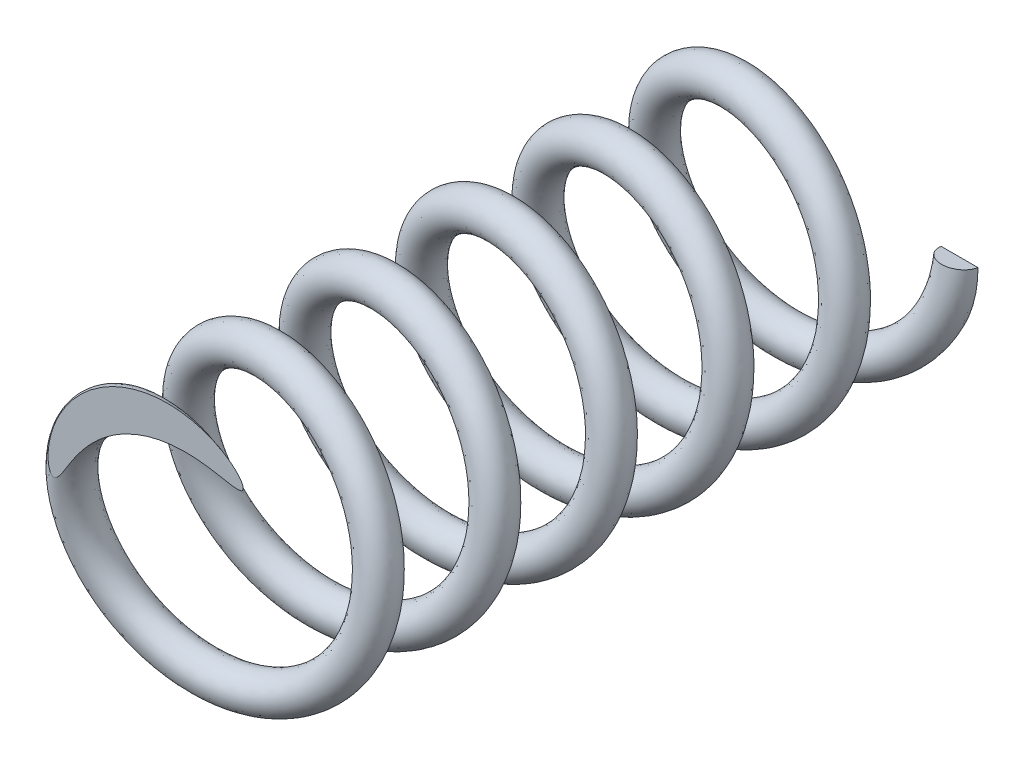
SolidWorks part; units mm, degrees
material "Alloy Steel"
ref_plane "Front Plane" through (0, 0, 0) normal (0, 0, 1) x (1, 0, 0)
ref_plane "Top Plane" through (0, 0, 0) normal (0, 1, 0) x (1, 0, 0)
ref_plane "Right Plane" through (0, 0, 0) normal (1, 0, 0) x (0, 0, -1)
ref_plane "Plane1" through (0, 0, 0) normal (0, 0, 1) x (1, 0, 0)
ref_plane "Plane2" through (0, 0, 108) normal (0, 0, -1) x (-1, 0, 0)
sketch "Sketch77" plane through (0, 0, 0) normal (0, 1, 0) x (1, 0, 0)
  line L0 (0, 0) -> (0, -108)
  line L1 (6, -108) -> (-6, -108) construction
  dimension "D1" = 108
ref_plane "Plane4" through (0, 0, 0) normal (0, 0, 1) x (1, 0, 0)
sketch "Sketch80" plane through (0, 0, 0) normal (0, 0, 1) x (1, 0, 0)
  circle A0 centre (0, 0) radius 20
  dimension "D1" = 40
curve "Helix/Spiral2" pitch 19 height 133 turns 7
ref_plane "Plane5" through (20, 0, 0) normal (0, -0.9888, 0.1495) x (-1, 0, 0)
sketch "Sketch83" plane through (20, 0, 0) normal (0, -0.9888, 0.1495) x (-1, 0, 0)
  circle A0 centre (0, 0) radius 3
  point P0 (0, 0)
  dimension "D1" = 6
sweep "Sweep2" add profiles "Sketch83" path "Helix/Spiral2"
sketch "Sketch85" plane through (0, 0, 0) normal (0, 0, 1) x (1, 0, 0)
  line L1 (-35, 35) -> (35, 35)
  line L2 (-35, 35) -> (-35, -35)
  line L3 (-35, -35) -> (35, -35)
  line L4 (35, 35) -> (35, -35)
  line L5 (-35, 35) -> (35, -35) construction
  line L6 (-35, -35) -> (35, 35) construction
  point P0 (0, 0)
  dimension "D1" = 70
  dimension "D2" = 70
extrude "Cut-Extrude3" cut sketch "Sketch85" against normal up to next
sketch "Sketch86" plane through (0, 0, 108) normal (0, 0, -1) x (-1, 0, 0)
  line L1 (35, -35) -> (-35, -35)
  line L2 (35, -35) -> (35, 35)
  line L3 (35, 35) -> (-35, 35)
  line L4 (-35, -35) -> (-35, 35)
  line L5 (35, -35) -> (-35, 35) construction
  line L6 (35, 35) -> (-35, -35) construction
  point P0 (0, 0)
  dimension "D1" = 70
  dimension "D2" = 70
extrude "Cut-Extrude4" cut sketch "Sketch86" against normal up to next
equation "\"wireDiameter\"= 6"
equation "\"D1@Sketch83\"=\"wireDiameter\""
equation "\"meanDiameter\"= 40"
equation "\"D1@Sketch80\"=\"meanDiameter\""
